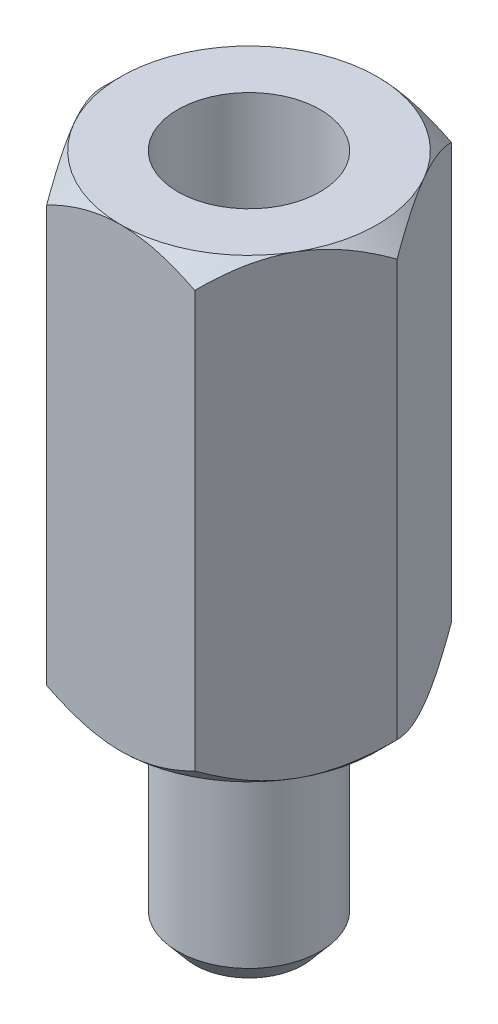
SolidWorks part; units mm, degrees
ref_plane "Front Plane" through (0, 0, 0) normal (0, 0, 1) x (1, 0, 0)
ref_plane "Top Plane" through (0, 0, 0) normal (0, 1, 0) x (1, 0, 0)
ref_plane "Right Plane" through (0, 0, 0) normal (1, 0, 0) x (0, 0, -1)
sketch "Sketch1" plane through (0, 0, 0) normal (0, 1, 0) x (1, 0, 0)
  circle A0 centre (0, 0) radius 1.25
  dimension "D1" = 2.5
extrude "Boss-Extrude1" add sketch "Sketch1" along normal blind 3.9
sketch "Sketch2" plane through (0, 3.9, 0) normal (0, 1, 0) x (1, 0, 0)
  line L1 (2.5981, 0) -> (1.299, 2.25)
  line L2 (1.299, 2.25) -> (-1.299, 2.25)
  line L3 (-1.299, 2.25) -> (-2.5981, 0)
  line L4 (-2.5981, 0) -> (-1.299, -2.25)
  line L5 (-1.299, -2.25) -> (1.299, -2.25)
  line L6 (1.299, -2.25) -> (2.5981, 0)
  circle A0 centre (0, 0) radius 2.25 construction
  point P1 (0, 0)
  dimension "D1" = 4.5
extrude "Boss-Extrude2" add sketch "Sketch2" along normal blind 8
sketch "Sketch3" plane through (0, 11.9, 0) normal (0, 1, 0) x (1, 0, 0)
  circle A0 centre (0, 0) radius 1.25
  dimension "D1" = 2.5
extrude "Cut-Extrude1" cut sketch "Sketch3" against normal blind 4.8
sketch "Sketch5" plane through (0, 11.9, 0) normal (0, 1, 0) x (1, 0, 0)
  line L0 (1.299, 2.25) -> (-1.299, 2.25) construction
  circle A0 centre (0, 0) radius 2.25
extrude "Cut-Extrude3" cut sketch "Sketch5" against normal through all draft 45 flip side to cut
sketch "Sketch6" plane through (0, 3.9, 0) normal (0, -1, 0) x (1, 0, 0)
  line L0 (-1.299, 2.25) -> (1.299, 2.25) construction
  circle A0 centre (0, 0) radius 2.25
extrude "Cut-Extrude6" cut sketch "Sketch6" against normal through all draft 45 flip side to cut
chamfer "Chamfer1" distance 0.3 angle 50 1 edges at (0, 0, 1.25)
